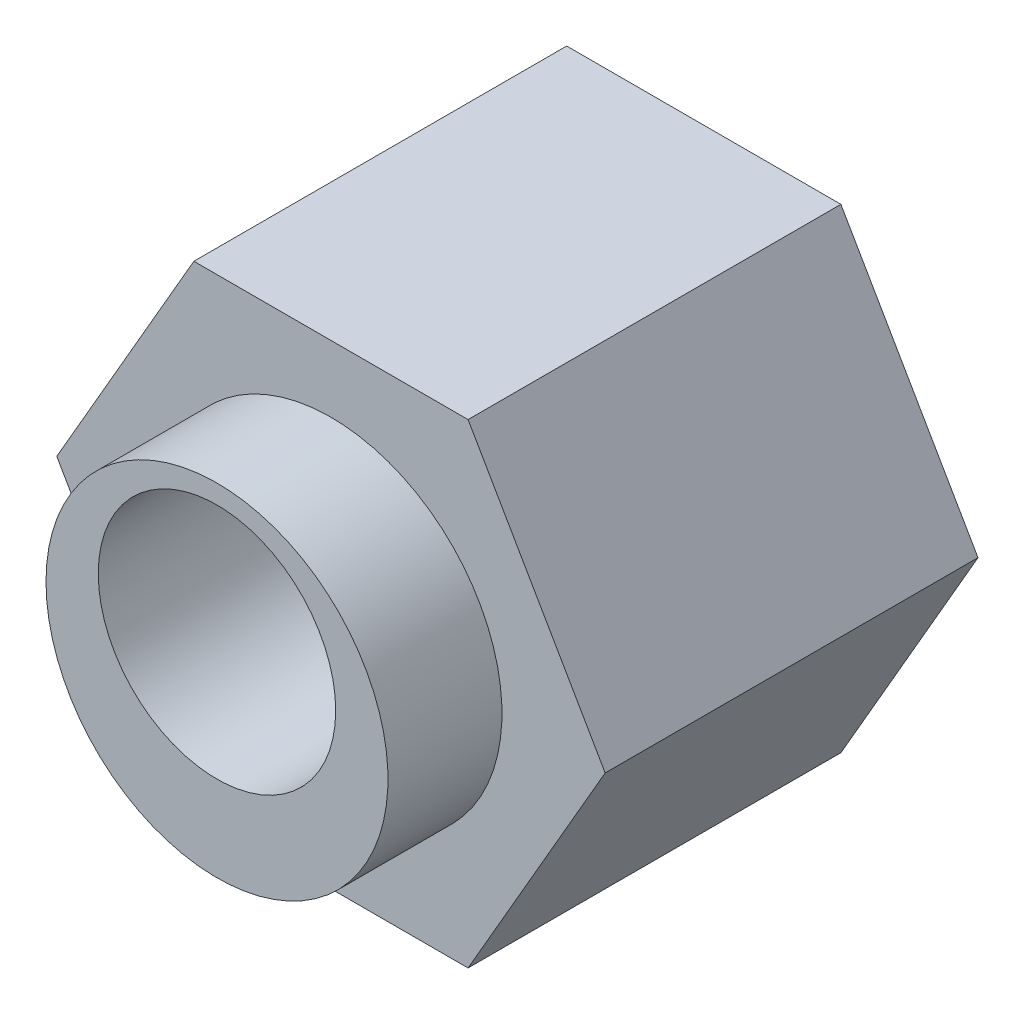
SolidWorks part; units mm, degrees
ref_plane "Ebene vorne" through (0, 0, 0) normal (0, 0, 1) x (1, 0, 0)
ref_plane "Ebene oben" through (0, 0, 0) normal (0, 1, 0) x (1, 0, 0)
ref_plane "Ebene rechts" through (0, 0, 0) normal (1, 0, 0) x (0, 0, -1)
ref_plane "Plane1" through (0, 0, 0.45) normal (0, 0, -1) x (-1, 0, 0)
sketch "Sketch1" plane through (0, 0, 0.45) normal (0, 0, -1) x (-1, 0, 0)
  line L0 (2.8868, -5) -> (5.7735, 0)
  line L1 (5.7735, 0) -> (2.8868, 5)
  line L2 (2.8868, 5) -> (-2.8868, 5)
  line L3 (-2.8868, 5) -> (-5.7735, 0)
  line L4 (-5.7735, 0) -> (-2.8868, -5)
  line L5 (-2.8868, -5) -> (2.8868, -5)
extrude "Boss-Extrude1" add sketch "Sketch1" against normal blind 7.85
ref_plane "Plane2" through (0, 0, 0) normal (0, -1, 0) x (1, 0, 0)
sketch "Sketch2" plane through (0, 0, 0) normal (0, -1, 0) x (1, 0, 0)
  line L0 (3.6, 10.7) -> (0, 10.7)
  line L1 (0, 10.7) -> (0, 8.3)
  line L2 (0, 8.3) -> (3.6, 8.3)
  line L3 (3.6, 8.3) -> (3.6, 10.7)
  line L4 (0, 10.7) -> (0, 8.3) construction
revolve "Revolve1" add sketch "Sketch2" angle 360 about L4
ref_plane "Plane3" through (0, 0.7, 0) normal (0, -1, 0) x (1, 0, 0)
sketch "Sketch3" plane through (0, 0.7, 0) normal (0, -1, 0) x (1, 0, 0)
  line L0 (3.6, 0.45) -> (0, 0.45)
  line L1 (0, 0.45) -> (0, -0.05)
  line L2 (0, -0.05) -> (3.6, -0.05)
  line L3 (3.6, -0.05) -> (3.6, 0.45)
  line L4 (0, 0.45) -> (0, -0.05) construction
revolve "Revolve2" add sketch "Sketch3" angle 360 about L4
hole_wizard "Ø5.0 (5) Diameter Hole1" positions "Sketch5" profile "Sketch4" hole size "Ø5.0" standard "ANSI Metric"
sketch "Sketch5" plane through (0, 0, -0.05) normal (0, 0, -1) x (-1, 0, 0)
  point P0 (0, 0.7)
sketch "Sketch4" plane through (0, 0.7, -0.05) normal (1, 0, 0) x (0, 1, 0)
  line L0 (0, 0) -> (0, 10.75)
  line L1 (0, 10.75) -> (2.5, 10.75)
  line L2 (2.5, 10.75) -> (2.5, 0)
  line L5 (2.5, 0) -> (0, 0)
  line L11 (0, -6.35) -> (0, 107.95) construction
  dimension "Thru Hole Dia." = 5
  dimension "Thru Hole Depth" = 10.75
chamfer "Chamfer1" distance 0.1 angle 45 2 edges at (-2.5, 0.7, -0.05) (-3.6, 0.7, -0.05)
